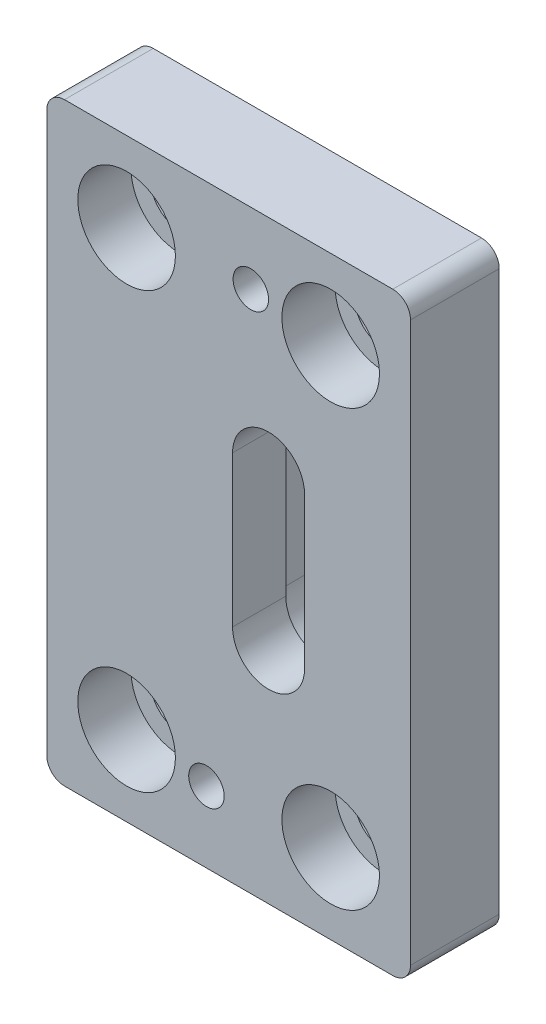
SolidWorks part; units mm, degrees
ref_plane "FP" through (0, 0, 0) normal (0, 0, 1) x (1, 0, 0)
ref_plane "TP" through (0, 0, 0) normal (0, 1, 0) x (1, 0, 0)
ref_plane "RP" through (0, 0, 0) normal (1, 0, 0) x (0, 0, -1)
ref_plane "Plane1" through (0, 0, 0) normal (0, 0, 1) x (1, 0, 0)
sketch "Sketch2" plane through (0, 0, 0) normal (0, 0, 1) x (1, 0, 0)
  line L0 (4, 5) -> (4, 22) construction
  line L1 (-23, 47) -> (14, 47)
  line L2 (-25, 45) -> (-25, -18)
  line L3 (-23, -20) -> (14, -20)
  line L4 (16, 45) -> (16, -18)
  line L5 (-4, 22) -> (-4, 5) construction
  line L10 (-4.06, 22) -> (-4.06, 5)
  line L11 (4.06, 5) -> (4.06, 22)
  line L12 (-4.06, 22) -> (-4.06, 5)
  line L13 (4.06, 5) -> (4.06, 22)
  arc A0 (-4, 5) -> (4, 5) centre (0, 5) ccw construction
  arc A1 (4, 22) -> (-4, 22) centre (0, 22) ccw construction
  arc A3 (-23, 47) -> (-25, 45) centre (-23, 45) ccw
  arc A4 (-25, -18) -> (-23, -20) centre (-23, -18) ccw
  arc A5 (14, -20) -> (16, -18) centre (14, -18) ccw
  arc A6 (14, 47) -> (16, 45) centre (14, 45) cw
  arc A7 (4.06, 22) -> (-4.06, 22) centre (0, 22) ccw
  arc A8 (-4.06, 5) -> (4.06, 5) centre (0, 5) ccw
  arc A9 (4.06, 22) -> (-4.06, 22) centre (0, 22) ccw
  arc A10 (-4.06, 5) -> (4.06, 5) centre (0, 5) ccw
  point P7 (0, 1)
  point P11 (0, 26)
  dimension "D5" = 0.06
  dimension "D6" = 2
  dimension "D1" = 21
  dimension "D2" = 21
  dimension "D3" = 12
  dimension "D4" = 21
extrude "Boss-Extrude1" add sketch "Sketch2" against normal blind 10
sketch "Sketch3" plane through (0, 0, 0) normal (0, 0, 1) x (1, 0, 0)
  line L4 (-5.06, 22) -> (-5.06, 5)
  line L5 (5.06, 5) -> (5.06, 22)
  line L6 (-5.06, 22) -> (-5.06, 5)
  line L7 (5.06, 5) -> (5.06, 22)
  arc A4 (-5.06, 5) -> (5.06, 5) centre (0, 5) ccw
  arc A5 (5.06, 22) -> (-5.06, 22) centre (0, 22) ccw
  arc A6 (-5.06, 5) -> (5.06, 5) centre (0, 5) ccw
  arc A7 (5.06, 22) -> (-5.06, 22) centre (0, 22) ccw
  dimension "D1" = 1
extrude "Cut-Extrude1" cut sketch "Sketch3" against normal blind 4 from offset 6 offset against normal yes
hole_wizard "CBORE for M6 SHCS1" positions "Sketch4" profile "Sketch5" counterbore size "M6" standard "ANSI Metric" end condition through all
sketch "Sketch4" plane through (0, 0, 0) normal (0, 0, 1) x (0.9063, -0.4226, 0)
  point P0 (-30.5604, 27.6778)
  point P1 (10.993, -7.0111)
  point P2 (-9.8521, -16.7313)
  point P3 (-9.7153, 37.398)
sketch "Sketch5" plane through (-16, 38, 0) normal (1, 0, 0) x (0, -1, 0)
  line L0 (0, 0) -> (0, 10)
  line L1 (0, 10) -> (3.3, 10)
  line L2 (3.3, 10) -> (3.3, 6)
  line L3 (3.3, 6) -> (5.5, 6)
  line L4 (5.5, 6) -> (5.5, 0)
  line L5 (5.5, 0) -> (0, 0)
  line L6 (0, -6.35) -> (0, 107.95) construction
  dimension "Thru Hole Dia." = 6.6
  dimension "Thru Hole Depth" = 10
  dimension "C'Bore Dia." = 11
  dimension "C'Bore Depth" = 6
hole_wizard "Ø4.0mm Clearance Dowel Hole1" positions "Sketch6" profile "Sketch7" hole size "Ø4.0" standard "ANSI Metric" end condition through all
sketch "Sketch6" plane through (0, 0, 0) normal (0, 0, 1) x (0.9063, -0.4226, 0)
  point P0 (-18.2947, 34.5008)
  point P1 (-1.2727, -13.834)
sketch "Sketch7" plane through (-2, 39, 0) normal (1, 0, 0) x (0, -1, 0)
  line L0 (0, 0) -> (0, 10)
  line L1 (0, 10) -> (2, 10)
  line L2 (2, 10) -> (2, 0)
  line L3 (2, 0) -> (0, 0)
  line L4 (0, -6.35) -> (0, 107.95) construction
  dimension "Thru Hole Dia." = 4
  dimension "Thru Hole Depth" = 10
